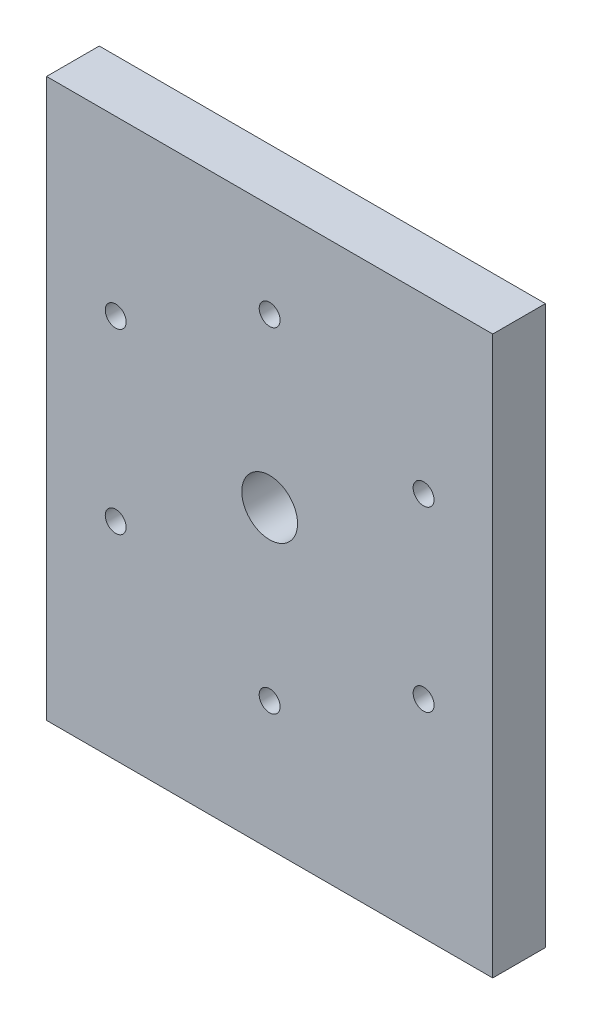
SolidWorks part; units mm, degrees
material "Acrylic (Medium-high impact)"
ref_plane "Front Plane" through (0, 0, 0) normal (0, 0, 1) x (1, 0, 0)
ref_plane "Top Plane" through (0, 0, 0) normal (0, 1, 0) x (1, 0, 0)
ref_plane "Right Plane" through (0, 0, 0) normal (1, 0, 0) x (0, 0, -1)
sketch "Sketch1" plane through (0, 0, 0) normal (0, 0, 1) x (1, 0, 0)
  line L0 (34.1802, 50.5429) -> (34.1802, 53.0508) construction
  line L1 (-50.8, 127) -> (50.8, 127)
  line L2 (-50.8, 127) -> (-50.8, 0)
  line L3 (-50.8, 0) -> (50.8, 0)
  line L4 (50.8, 127) -> (50.8, 0)
  circle A0 centre (0, 67.375) radius 6.35
  circle A7 centre (0, 67.375) radius 38.1 construction
  dimension "D1" = 127
  dimension "D3" = 12.7
  dimension "D12" = 76.2
  dimension "D2" = 101.6
  dimension "D5" = 67.375
extrude "Boss-Extrude1" add sketch "Sketch1" along normal blind 12
sketch "Sketch2" plane through (0, 0, 0) normal (0, 0, -1) x (-1, 0, 0)
  line L0 (0, 67.375) -> (-35.0578, 87.6156) construction
  line L1 (-32.9956, 48.325) -> (-32.9956, 86.425) construction
  line L2 (-32.9956, 86.425) -> (0, 105.475) construction
  line L3 (0, 105.475) -> (32.9956, 86.425) construction
  line L4 (32.9956, 86.425) -> (32.9956, 48.325) construction
  line L5 (32.9956, 48.325) -> (0, 29.275) construction
  line L6 (0, 29.275) -> (-32.9956, 48.325) construction
  line L7 (0, 67.375) -> (-35.0578, 47.1344) construction
  line L8 (0, 67.375) -> (35.0578, 47.1344) construction
  line L9 (0, 67.375) -> (35.0578, 87.6156) construction
  circle A3 centre (0, 67.375) radius 38.1 construction
  circle A5 centre (0, 105.475) radius 2.3812
  circle A6 centre (0, 29.275) radius 2.3813
  circle A7 centre (-35.0578, 87.6156) radius 2.3812
  circle A8 centre (-35.0578, 47.1344) radius 2.3812
  circle A9 centre (35.0578, 47.1344) radius 2.3812
  circle A10 centre (35.0578, 87.6156) radius 2.3812
  dimension "D1" = 76.2
  dimension "D2" = 4.7625
  dimension "D3" = 4.7625
extrude "Cut-Extrude1" cut sketch "Sketch2" against normal through all
sketch "Sketch3" plane through (0, 0, 0) normal (0, -1, 0) x (1, 0, 0)
  line L0 (31.75, 6) -> (-31.75, 6) construction
  line L2 (0, 0) -> (0, 12) construction
  line L3 (-50.8, 12) -> (50.8, 12) construction
  circle A0 centre (31.75, 6) radius 1.27
  circle A1 centre (0, 6) radius 1.27
  circle A2 centre (-31.75, 6) radius 1.27
  point P9 (0, 6)
  dimension "D2" = 2.54
  dimension "D1" = 31.75
extrude "Cut-Extrude2" cut sketch "Sketch3" against normal blind 12.7
hole_wizard "#10-32 Tapped Hole3" positions "Sketch11" profile "Sketch13" tap size "#10-32" standard "ANSI Inch"
sketch "Sketch11" plane through (0, 0, 0) normal (0, -1, 0) x (-1, 0, 0)
  point P0 (-31.75, -6)
  point P3 (0, -6)
  point P6 (31.75, -6)
sketch "Sketch13" plane through (31.75, 0, 6) normal (1, 0, 0) x (0, 0, -1)
  line L0 (0, 0) -> (0, 13.9133)
  line L1 (0, 13.9133) -> (2.0193, 12.7)
  line L2 (2.0193, 12.7) -> (2.0193, 0)
  line L5 (2.0193, 0) -> (0, 0)
  line L10 (0, 13.9133) -> (-2.0193, 12.7) construction
  line L11 (0, -6.35) -> (0, 107.95) construction
  dimension "Tap Drill Dia." = 4.0386
  dimension "Tap Drill Depth" = 12.7
  dimension "Drill Angle" = 118
cosmetic thread "Hole Thread11" parameters "D1"=10.16, "D2"=4.826
cosmetic thread "Hole Thread12" parameters "D1"=10.16, "D2"=4.826
cosmetic thread "Hole Thread13" parameters "D1"=10.16, "D2"=4.826
